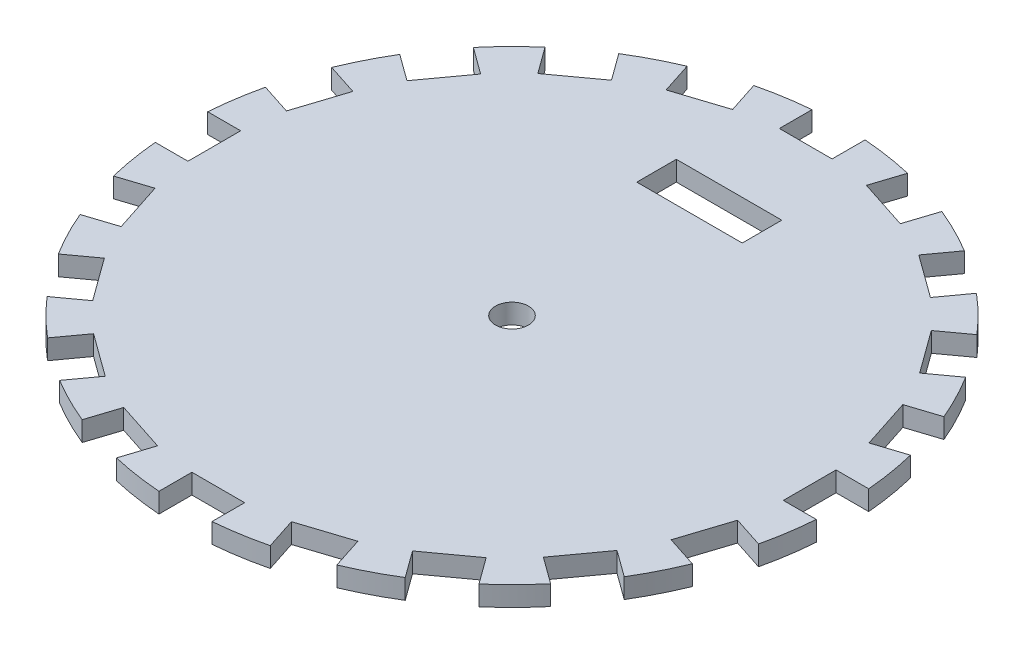
SolidWorks part; units mm, degrees
ref_plane "Front Plane" through (0, 0, 0) normal (0, 0, 1) x (1, 0, 0)
ref_plane "Top Plane" through (0, 0, 0) normal (0, 1, 0) x (1, 0, 0)
ref_plane "Right Plane" through (0, 0, 0) normal (1, 0, 0) x (0, 0, -1)
sketch "Sketch1" plane through (0, 0, 0) normal (0, 1, 0) x (1, 0, 0)
  circle A0 centre (0, 0) radius 50
  dimension "D1" = 100
extrude "Boss-Extrude3" add sketch "Sketch1" along normal blind 3 contours A0
sketch "Sketch7" plane through (0, 3, 0) normal (0, 1, 0) x (1, 0, 0)
  circle A0 centre (0, 0) radius 2.5
  dimension "D1" = 5
extrude "Cut-Extrude1" cut sketch "Sketch7" against normal blind 3
sketch "Sketch8" plane through (0, 3, 0) normal (0, 1, 0) x (1, 0, 0)
  line L0 (0, 0) -> (0, 50) construction
  line L1 (-4.3009, 44.863) -> (3.6991, 44.863)
  line L6 (3.6991, 49.863) -> (3.6991, 44.863)
  line L7 (-4.3009, 44.863) -> (-4.3009, 49.8147)
  circle A0 centre (0, 0) radius 50 construction
  dimension "D1" = 8
  dimension "D2" = 5
extrude "Cut-Extrude4" cut sketch "Sketch8" against normal blind 3 and the other way through all flip side to cut
pattern_circular "CirPattern5" count 20 over 360 about axis through (0, 3, 0) along (0, 1, 0) of "Cut-Extrude4"
sketch "Sketch9" plane through (0, 3, 0) normal (0, 1, 0) x (1, 0, 0)
  line L3 (7.9304, 27) -> (-8.0696, 27)
  line L4 (7.9304, 27) -> (7.9304, 33)
  line L5 (7.9304, 33) -> (-8.0696, 33)
  line L6 (-8.0696, 27) -> (-8.0696, 33)
  line L7 (7.9304, 27) -> (-8.0696, 33) construction
  line L8 (7.9304, 33) -> (-8.0696, 27) construction
  point P5 (-0.0696, 30)
  dimension "D1" = 30
  dimension "D2" = 16
  dimension "D3" = 6
extrude "Cut-Extrude5" cut sketch "Sketch9" against normal blind 3
